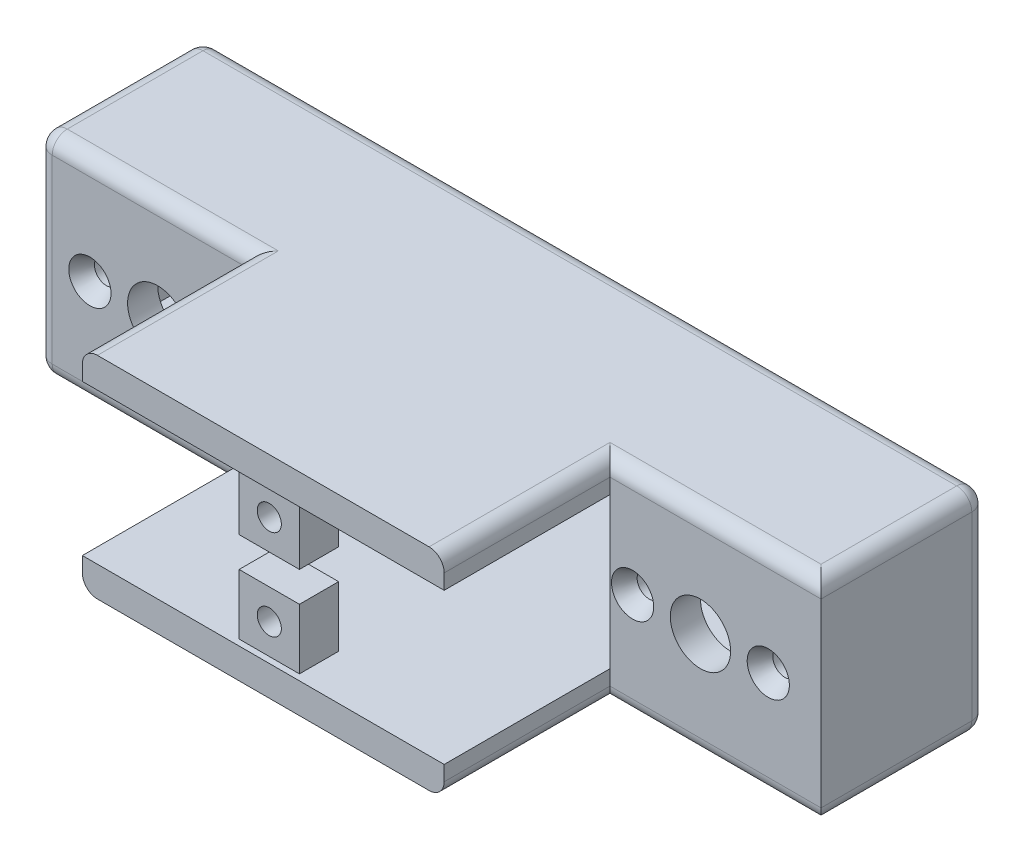
SolidWorks part; units mm, degrees
ref_plane "Front Plane" through (0, 0, 0) normal (0, 0, 1) x (1, 0, 0)
ref_plane "Top Plane" through (0, 0, 0) normal (0, 1, 0) x (1, 0, 0)
ref_plane "Right Plane" through (0, 0, 0) normal (1, 0, 0) x (0, 0, -1)
sketch "草图1" plane through (0, 0, 0) normal (0, 0, 1) x (1, 0, 0)
  line L1 (0, 0) -> (52, 0)
  line L2 (0, 0) -> (0, 14)
  line L3 (0, 14) -> (52, 14)
  line L4 (52, 0) -> (52, 14)
extrude "凸台-拉伸1" add sketch "草图1" along normal blind 11
shell "抽壳1" thickness 2
sketch "草图2" plane through (0, 0, 9) normal (0, 0, -1) x (-1, 0, 0)
  line L1 (-14, 12) -> (-38, 12)
  line L2 (-14, 12) -> (-14, 2)
  line L3 (-14, 2) -> (-38, 2)
  line L4 (-38, 12) -> (-38, 2)
extrude "切除-拉伸1" cut sketch "草图2" against normal blind 2
sketch "草图3" plane through (0, 0, 11) normal (0, 0, 1) x (1, 0, 0)
  line L0 (52, 14) -> (0, 14) construction
  line L1 (38, 2) -> (14, 2)
  line L2 (38, 2) -> (38, 0)
  line L3 (38, 0) -> (14, 0)
  line L4 (14, 2) -> (14, 0)
  line L5 (14, 12) -> (38, 12)
  line L6 (14, 12) -> (14, 14)
  line L7 (14, 14) -> (38, 14)
  line L8 (38, 12) -> (38, 14)
extrude "凸台-拉伸2" add sketch "草图3" along normal blind 11
sketch "草图8" plane through (0, 0, 11) normal (0, 0, 1) x (1, 0, 0)
  circle A0 centre (8, 7) radius 2
  circle A1 centre (44, 7) radius 2
extrude "切除-拉伸5" cut sketch "草图8" against normal blind 2
fillet "圆角1" radius 1 17 edges at (38, 0, 16.5) (38, 14, 16.5) (14, 14, 16.5) (14, 0, 16.5) (45, 0, 11) (45, 14, 11) (7, 0, 11) (7, 14, 11) (0, 7, 11) (0, 7, 0) (26, 0, 0) (26, 14, 0) (52, 7, 0) (52, 0, 5.5) (52, 14, 5.5) (0, 14, 5.5) (0, 0, 5.5)
sketch "草图15" plane through (0, 0, 22) normal (0, 0, 1) x (1, 0, 0)
  line L1 (24, 2) -> (28, 2)
  line L2 (24, 2) -> (24, 6)
  line L3 (24, 6) -> (28, 6)
  line L4 (28, 2) -> (28, 6)
  line L5 (24, 8) -> (28, 8)
  line L6 (24, 8) -> (24, 12)
  line L7 (24, 12) -> (28, 12)
  line L8 (28, 8) -> (28, 12)
sketch "草图16" plane through (0, 0, 22) normal (0, 0, 1) x (1, 0, 0)
  circle A0 centre (26, 10) radius 0.8
  circle A1 centre (26, 4) radius 0.8
extrude "凸台-拉伸4" add sketch "草图15" against normal blind 3
extrude "切除-拉伸7" cut sketch "草图16" against normal blind 3
sketch "草图17" plane through (0, 0, 22) normal (0, 0, 1) x (1, 0, 0)
  line L1 (38, 2) -> (14, 2)
  line L2 (38, 2) -> (38, 12)
  line L3 (38, 12) -> (14, 12)
  line L4 (14, 2) -> (14, 12)
ref_plane "基准面1" through (0, 7, 0) normal (0, 1, 0) x (1, 0, 0)
sketch "草图19" plane through (0, 7, 0) normal (0, 1, 0) x (1, 0, 0)
  line L0 (2.1, -11) -> (3.5, -11)
  line L3 (2.7, -9.9) -> (2.1, -11)
  line L4 (2.7, -9.9) -> (2.7, -9)
  line L5 (3.5, -11) -> (3.5, -9)
  line L6 (2.7, -9) -> (3.5, -9)
sketch "草图20" plane through (0, 7, 0) normal (0, 1, 0) x (1, 0, 0)
  line L0 (11.1, -11) -> (12.5, -11)
  line L1 (11.1, -11) -> (11.7, -9.9)
  line L2 (11.7, -9.9) -> (11.7, -9)
  line L3 (12.5, -11) -> (12.5, -9)
  line L4 (11.7, -9) -> (12.5, -9)
sketch "草图21" plane through (0, 7, 0) normal (0, 1, 0) x (1, 0, 0)
  line L0 (38.1, -11) -> (39.5, -11)
  line L1 (38.1, -11) -> (38.7, -9.9)
  line L2 (38.7, -9.9) -> (38.7, -9)
  line L3 (39.5, -11) -> (39.5, -9)
  line L4 (38.7, -9) -> (39.5, -9)
sketch "草图22" plane through (0, 7, 0) normal (0, 1, 0) x (1, 0, 0)
  line L0 (47.1, -11) -> (48.5, -11)
  line L1 (47.1, -11) -> (47.7, -9.9)
  line L2 (48.5, -11) -> (48.5, -9)
  line L3 (47.7, -9.9) -> (47.7, -9)
  line L4 (47.7, -9) -> (48.5, -9)
revolve "切除-旋转6" cut sketch "草图19" angle 360 about L5
revolve "切除-旋转7" cut sketch "草图20" angle 360 about L3
revolve "切除-旋转8" cut sketch "草图21" angle 360 about L3
revolve "切除-旋转9" cut sketch "草图22" angle 360 about L2
extrude "切除-拉伸8" cut sketch "草图17" against normal blind 0.4
